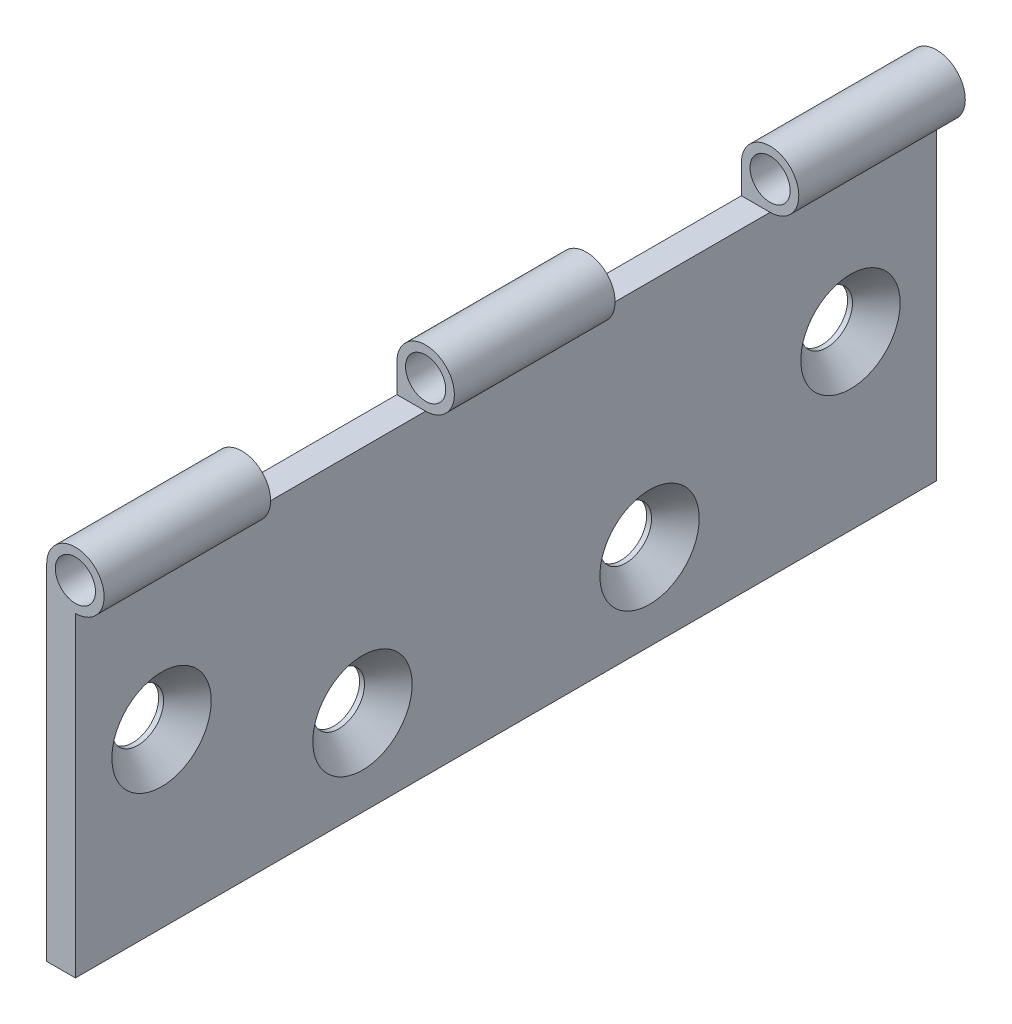
SolidWorks part; units mm, degrees
ref_plane "Front" through (0, 0, 0) normal (0, 0, 1) x (1, 0, 0)
ref_plane "Top" through (0, 0, 0) normal (0, 1, 0) x (1, 0, 0)
ref_plane "Right" through (0, 0, 0) normal (1, 0, 0) x (0, 0, -1)
sketch "Sketch1" plane through (0, 0, 0) normal (0, 0, 1) x (1, 0, 0)
  line L0 (0, 0) -> (0, 60)
  dimension "D1" = 60
extrude "Extrude-Thin1" add sketch "Sketch1" along normal mid plane 150 thin
sketch "Sketch2" plane through (0, 0, 75) normal (0, 0, 1) x (1, 0, 0)
  line L3 (0, 0) -> (0, 60) construction
  circle A0 centre (5, 60) radius 5
sweep "Sweep1" add profiles "Sketch2" path edge at (5, 60, 0)
sketch "Sketch3" plane through (0, 0, 75) normal (0, 0, 1) x (1, 0, 0)
  circle A0 centre (5, 60) radius 3.5
  dimension "D1" = 7
extrude "Cut-Extrude1" cut sketch "Sketch3" against normal through all
hole_wizard "CSK for M8 Flat Head Machine Screw1" positions "Sketch4" profile "Sketch5" countersink size "M8" standard "ANSI Metric" end condition through all
sketch "Sketch4" plane through (5, 0, 0) normal (1, 0, 0) x (0, 0, -1)
  line L0 (-75, 0) -> (75, 0) construction
  line L1 (-75, 0) -> (-75, 55) construction
  point P0 (-25, 15)
  point P2 (-60, 30)
  dimension "D1" = 30
  dimension "D2" = 15
  dimension "D3" = 50
  dimension "D4" = 15
sketch "Sketch5" plane through (5, 15, 25) normal (0, 1, 0) x (0, 0, -1)
  line L0 (0, 0) -> (0, 5)
  line L1 (0, 5) -> (4.5, 5)
  line L2 (4.5, 5) -> (4.5, 4.15)
  line L3 (4.5, 4.15) -> (8.65, 0)
  line L5 (8.65, 0) -> (0, 0)
  line L6 (-4.5, 4.15) -> (-8.65, 0) construction
  line L11 (0, -6.35) -> (0, 107.95) construction
  dimension "Thru Hole Dia." = 9
  dimension "Thru Hole Depth" = 5
  dimension "Near C'Sink Dia." = 17.3
  dimension "Near C'Sink Angle" = 90
mirror "Mirror1" about plane through (0, 0, 0) normal (0, 0, 1) of "CSK for M8 Flat Head Machine Screw1"
sketch "layout for cuts" plane through (5, 0, 0) normal (1, 0, 0) x (0, 0, -1)
  line L0 (-75, 60) -> (-75, 55) construction
  line L1 (75, 55) -> (75, 60) construction
  line L2 (-75, 54) -> (75, 54)
  line L3 (-75, 54) -> (75, 54)
  line L4 (-75, 65) -> (-75, 60) construction
  line L5 (75, 60) -> (75, 65) construction
  line L6 (-75, 60) -> (-75, 54)
  line L7 (75, 54) -> (75, 60)
  line L8 (-75, 65) -> (-75, 60)
  line L9 (75, 60) -> (75, 65)
  line L10 (-75, 65) -> (75, 65)
  line L11 (-45, 54) -> (-45, 65)
  line L12 (-15, 54) -> (-15, 65)
  line L13 (0, 75.2446) -> (0, 0) construction
  line L14 (15, 54) -> (15, 65)
  line L15 (45, 54) -> (45, 65)
  dimension "D2" = 30
  dimension "D3" = 30
  dimension "D1" = 1
sketch "Sketch8" plane through (5, 0, 0) normal (1, 0, 0) x (0, 0, -1)
  line L0 (-75, 54) -> (75, 54) construction
  line L1 (75, 54) -> (75, 60) construction
  line L3 (-75, 65) -> (75, 65) construction
  line L4 (75, 55) -> (-75, 55)
  line L5 (-75, 55) -> (-75, 0)
  line L6 (-75, 0) -> (75, 0)
  line L7 (75, 0) -> (75, 55)
  line L8 (75, 55) -> (-75, 55)
  line L9 (-75, 55) -> (-75, 0)
  line L10 (-75, 0) -> (75, 0)
  line L11 (75, 0) -> (75, 55)
  line L13 (-75, 60) -> (-75, 54) construction
  line L14 (-46, 54) -> (-14, 54)
  line L15 (75, 54) -> (75, 55)
  line L17 (-46, 65) -> (-14, 65)
  line L18 (14, 65) -> (46, 65)
  line L19 (-75, 55) -> (-75, 54)
  line L22 (-46, 54) -> (-46, 65)
  line L23 (-46, 54) -> (-46, 65)
  line L25 (46, 54) -> (46, 65)
  line L26 (46, 54) -> (46, 65)
  line L28 (-14, 54) -> (-14, 65)
  line L29 (-14, 54) -> (-14, 65)
  line L30 (14, 54) -> (46, 54)
  line L31 (14, 54) -> (14, 65)
  line L32 (14, 54) -> (14, 65)
  line M13 (75, 55) -> (-75, 55)
  dimension "D1" = 0
  dimension "D2" = 1
  dimension "D3" = 1
  dimension "D4" = 1
  dimension "D5" = 1
extrude "2Cuts" cut sketch "Sketch8" against normal through all and the other way through all contours L29 L17 L23 M13 | L32 L8 L26 L18
sketch "Sketch7" plane through (5, 0, 0) normal (1, 0, 0) x (0, 0, -1)
  line L0 (-75, 54) -> (75, 54) construction
  line L1 (75, 54) -> (75, 60) construction
  line L2 (75, 60) -> (75, 65) construction
  line L3 (-75, 65) -> (75, 65) construction
  line L4 (75, 55) -> (46, 55)
  line L5 (-75, 55) -> (-75, 0)
  line L6 (-75, 0) -> (75, 0)
  line L7 (75, 0) -> (75, 55)
  line L8 (75, 55) -> (44, 55)
  line L9 (-75, 55) -> (-75, 0)
  line L10 (-75, 0) -> (75, 0)
  line L11 (75, 0) -> (75, 55)
  line L12 (-75, 65) -> (-75, 60) construction
  line L13 (-75, 60) -> (-75, 54) construction
  line L14 (-75, 54) -> (-44, 54)
  line L15 (75, 54) -> (75, 60)
  line L16 (75, 60) -> (75, 65)
  line L17 (-75, 65) -> (-44, 65)
  line L18 (-75, 65) -> (-75, 60)
  line L19 (-75, 60) -> (-75, 54)
  line L22 (-44, 54) -> (-44, 65)
  line L23 (-44, 54) -> (-44, 65)
  line L25 (44, 54) -> (44, 65)
  line L26 (44, 54) -> (44, 65)
  line L28 (16, 54) -> (16, 65)
  line L29 (16, 54) -> (16, 65)
  line L30 (-16, 65) -> (16, 65)
  line L31 (-16, 54) -> (-16, 65)
  line L32 (-16, 54) -> (-16, 65)
  line L33 (-44, 55) -> (134, 55)
  line L34 (-16, 54) -> (16, 54)
  line L35 (44, 65) -> (75, 65)
  line L36 (16, 55) -> (-16, 55)
  line L37 (44, 54) -> (75, 54)
  line L42 (-46, 55) -> (-75, 55)
  line L43 (-46, 55) -> (-75, 55)
  line L44 (46, 55) -> (14, 55)
  line L45 (46, 55) -> (14, 55)
  line L46 (14, 55) -> (-14, 55)
  line L47 (14, 55) -> (-14, 55)
  line L48 (-14, 55) -> (-46, 55)
  line L49 (-14, 55) -> (-46, 55)
  line M15 (75, 55) -> (46, 55)
  dimension "D1" = 0
  dimension "D2" = 1
  dimension "D3" = 1
  dimension "D4" = 1
  dimension "D5" = 1
extrude "3Cuts" [suppressed] cut sketch "Sketch7" against normal blind 10 and the other way through all contours L32 L29 L30 M15 | L35 L26 L15 L16 M15 | L23 L17 L18 L19 M15
equation "\"D1@Sketch4\"= \"D1@Sketch1\" / 2"
equation "\"D3@Sketch4\"= \"D1@Extrude-Thin1\" / 3"
equation "\"D2@layout for cuts\"= \"D1@Extrude-Thin1\" / 5"
equation "\"D3@layout for cuts\"= \"D1@Extrude-Thin1\" / 5"
